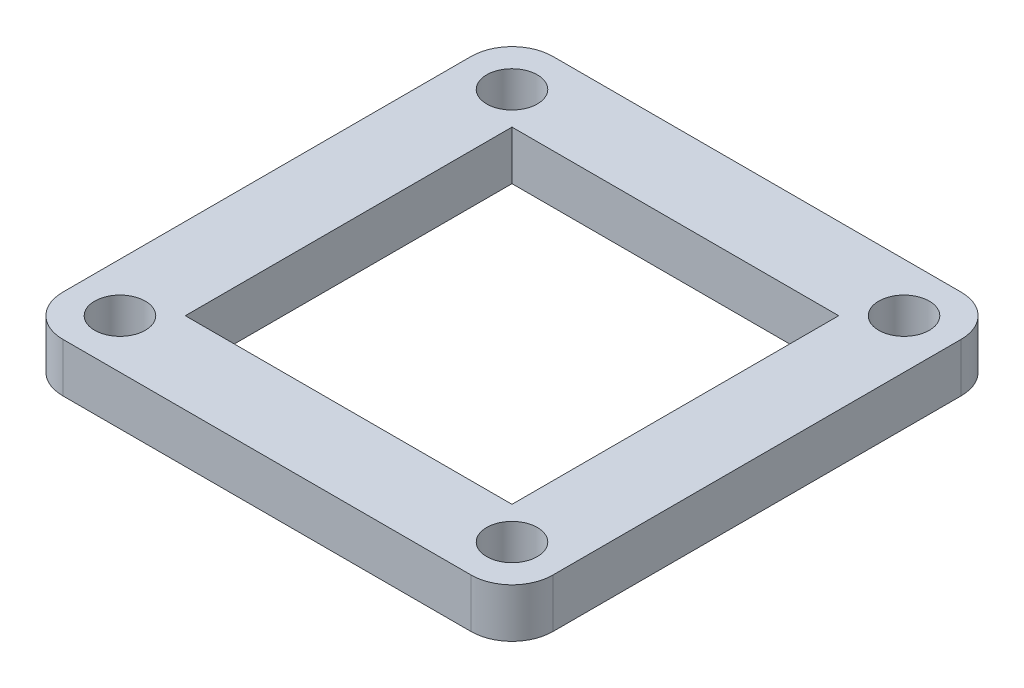
SolidWorks part; units mm, degrees
ref_plane "Front Plane" through (0, 0, 0) normal (0, 0, 1) x (1, 0, 0)
ref_plane "Top Plane" through (0, 0, 0) normal (0, 1, 0) x (1, 0, 0)
ref_plane "Right Plane" through (0, 0, 0) normal (1, 0, 0) x (0, 0, -1)
sketch "Sketch1" plane through (0, 0, 0) normal (0, 1, 0) x (1, 0, 0)
  line L1 (-15, -15) -> (15, -15)
  line L2 (-15, -15) -> (-15, 15)
  line L3 (-15, 15) -> (15, 15)
  line L4 (15, -15) -> (15, 15)
  line L5 (-15, -15) -> (15, 15) construction
  line L6 (-15, 15) -> (15, -15) construction
  line L7 (-10, 10) -> (10, 10)
  line L8 (-10, 10) -> (-10, -10)
  line L9 (-10, -10) -> (10, -10)
  line L10 (10, 10) -> (10, -10)
  line L11 (-10, 10) -> (10, -10) construction
  line L12 (-10, -10) -> (10, 10) construction
  circle A0 centre (12, 12) radius 1.55
  circle A1 centre (12, -12) radius 1.55
  circle A2 centre (-12, 12) radius 1.55
  circle A3 centre (-12, -12) radius 1.55
  point P0 (0, 0)
  point P12 (0, 0)
  dimension "D3" = 3.1
  dimension "D4" = 3.1
  dimension "D1" = 30
  dimension "D2" = 30
  dimension "D5" = 3
  dimension "D6" = 3
  dimension "D7" = 3
  dimension "D8" = 3
  dimension "D10" = 20
  dimension "D9" = 2
extrude "Boss-Extrude1" add sketch "Sketch1" along normal blind 3
fillet "Fillet2" radius 2.5 4 edges at (-15, 1.5, -15) (-15, 1.5, 15) (15, 1.5, 15) (15, 1.5, -15)
